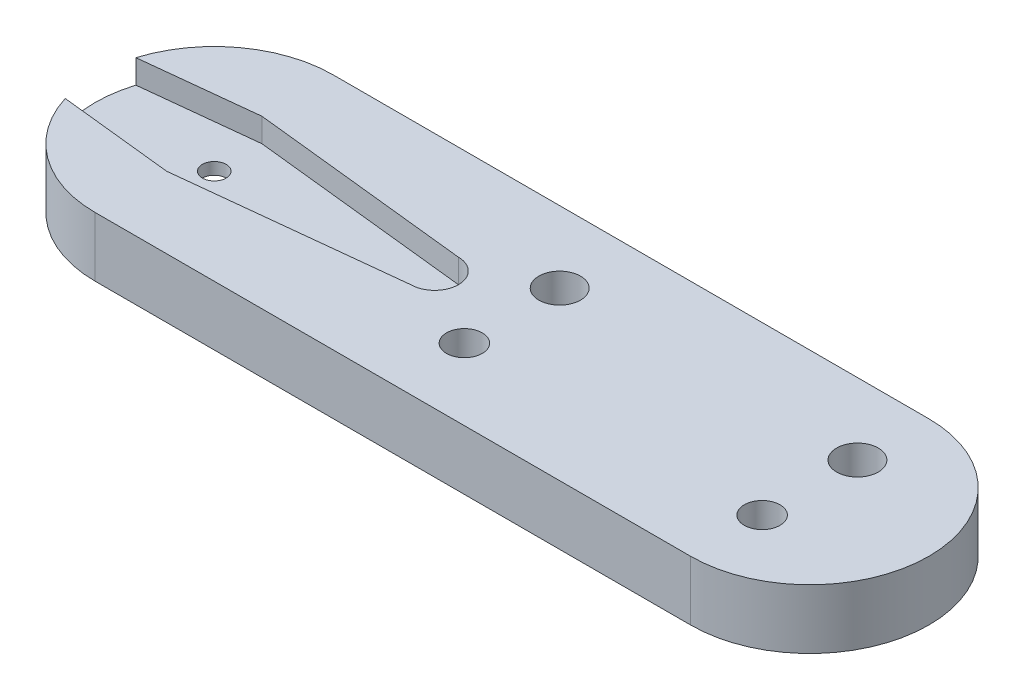
SolidWorks part; units mm, degrees
ref_plane "Front Plane" through (0, 0, 0) normal (0, 0, 1) x (1, 0, 0)
ref_plane "Top Plane" through (0, 0, 0) normal (0, 1, 0) x (1, 0, 0)
ref_plane "Right Plane" through (0, 0, 0) normal (1, 0, 0) x (0, 0, -1)
sketch "Sketch1" plane through (0, 0, 0) normal (0, 1, 0) x (1, 0, 0)
  line L1 (-25, 10) -> (25, 10)
  line L3 (-25, -10) -> (25, -10)
  arc A0 (25, -10) -> (25, 10) centre (25, 0) ccw
  arc A1 (-25, 10) -> (-25, -10) centre (-25, 0) ccw
  point P0 (0, 0)
  dimension "D1" = 20
  dimension "D2" = 50
extrude "Boss-Extrude1" add sketch "Sketch1" along normal blind 5
sketch "Sketch5" plane through (0, 5, 0) normal (0, 1, 0) x (1, 0, 0)
  line L0 (-25, 10) -> (-25, -10)
  circle A0 centre (-25, 0) radius 1
  dimension "D1" = 2
extrude "Cut-Extrude4" cut sketch "Sketch5" against normal through all contours L0 A0 | L0 A0
sketch "Sketch6" plane through (0, 5, 0) normal (0, 1, 0) x (1, 0, 0)
  line L0 (-43.8499, 1.9692) -> (-43.5, 2)
  line L1 (-43.5, 2) -> (-25, 4)
  line L2 (-25, 4) -> (-6.5, 2)
  line L3 (-43.5, -2) -> (-25, -4)
  line L4 (-25, -4) -> (-6.5, -2)
  arc A0 (-25.8549, -3.9076) -> (-24.1451, -3.9076) centre (-25, 0) ccw
  arc A1 (-43.5, 2) -> (-43.5, -2) centre (-43.5, 0) ccw
  arc A2 (-6.5, -2) -> (-6.5, 2) centre (-6.5, 0) ccw
  arc A3 (-24.1451, 3.9076) -> (-25.8549, 3.9076) centre (-25, 0) ccw
  point P3 (-6.5, 0)
  point P4 (-43.5, 0)
  dimension "D1" = 8
  dimension "D4" = 4
  dimension "D5" = 4
  dimension "D2" = 18.5
  dimension "D3" = 18.5
extrude "Cut-Extrude5" cut sketch "Sketch6" against normal blind 2 contours A1 L3 L4 A2 L2 L1
sketch "Sketch7" plane through (0, 0, 0) normal (0, -1, 0) x (1, 0, 0)
  circle A0 centre (-25, 0) radius 4
  dimension "D1" = 8
extrude "Cut-Extrude6" cut sketch "Sketch7" against normal blind 2
sketch "Sketch11" plane through (0, 5, 0) normal (0, 1, 0) x (1, 0, 0)
  line L0 (25, 10) -> (25, -10)
  circle A0 centre (25, 4) radius 1.75
  circle A1 centre (25, -4) radius 1.5
  point P4 (25, 0)
  point P5 (25, 4)
  point P6 (25, -4)
  dimension "D3" = 3.5
  dimension "D4" = 3
  dimension "D1" = 4
  dimension "D2" = 4
extrude "Cut-Extrude10" cut sketch "Sketch11" against normal through all contours L0 A0 | L0 A0 | L0 A1 | L0 A1
sketch "Sketch12" plane through (0, 5, 0) normal (0, 1, 0) x (1, 0, 0)
  circle A0 centre (0, 4) radius 1.75
  circle A1 centre (0, -4) radius 1.5
  point P0 (0, 0)
  point P1 (0, 4)
  point P3 (0, -4)
  dimension "D3" = 3.5
  dimension "D4" = 3
  dimension "D1" = 4
  dimension "D2" = 4
extrude "Cut-Extrude11" cut sketch "Sketch12" against normal through all
